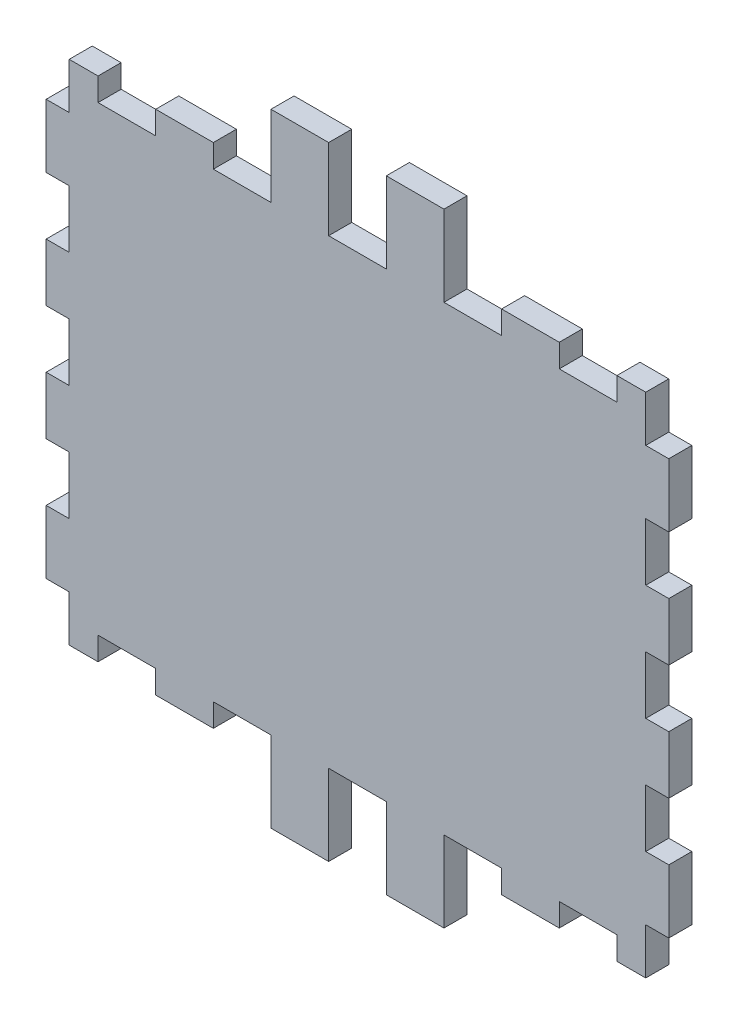
SolidWorks part; units mm, degrees
ref_plane "Front Plane" through (0, 0, 0) normal (0, 0, 1) x (1, 0, 0)
ref_plane "Top Plane" through (0, 0, 0) normal (0, 1, 0) x (1, 0, 0)
ref_plane "Right Plane" through (0, 0, 0) normal (1, 0, 0) x (0, 0, -1)
sketch "Sketch1" plane through (0, 0, 0) normal (0, 0, 1) x (1, 0, 0)
  line L0 (-50, 40) -> (-40, 40)
  line L1 (-50, -40) -> (50, -40)
  line L2 (-50, -40) -> (-50, 40)
  line L3 (-50, 40) -> (50, 40)
  line L4 (50, -40) -> (50, 40)
  line L5 (0, 40) -> (0, -40) construction
  line L6 (-50, 0) -> (50, 0) construction
  line L7 (-40, 40) -> (-30, 40)
  line L8 (-30, 40) -> (-20, 40)
  line L9 (-20, 40) -> (-10, 40)
  line L10 (-10, 40) -> (0, 40)
  line L11 (0, 40) -> (10, 40)
  line L12 (10, 40) -> (20, 40)
  line L13 (20, 40) -> (30, 40)
  line L14 (30, 40) -> (40, 40)
  line L15 (40, 40) -> (50, 40)
  line L16 (50, 20) -> (50, 0)
  line L17 (50, 0) -> (50, -20)
  line L18 (50, -20) -> (50, -40)
  line L19 (50, -40) -> (40, -40)
  line L20 (40, -40) -> (30, -40)
  line L21 (30, -40) -> (20, -40)
  line L22 (20, -40) -> (10, -40)
  line L23 (10, -40) -> (0, -40)
  line L24 (0, -40) -> (-10, -40)
  line L25 (-10, -40) -> (-20, -40)
  line L26 (-20, -40) -> (-30, -40)
  line L27 (-30, -40) -> (-40, -40)
  line L28 (-40, -40) -> (-50, -40)
  line L29 (-50, -20) -> (-50, 0)
  line L30 (-50, 0) -> (-50, 20)
  line L31 (-50, 20) -> (-50, 40)
  line L32 (50, -40) -> (50, -20) construction
  line L34 (-54, -35) -> (-46, -35)
  line L35 (-54, -35) -> (-54, -25)
  line L36 (-54, -25) -> (-46, -25)
  line L37 (-46, -35) -> (-46, -25)
  line L38 (-50, -25) -> (-50, -35) construction
  line L39 (-54, -30) -> (-46, -30) construction
  line L40 (-54, -15) -> (-46, -15)
  line L41 (-54, -15) -> (-54, -5)
  line L42 (-54, -5) -> (-46, -5)
  line L43 (-46, -15) -> (-46, -5)
  line L44 (-50, -5) -> (-50, -15) construction
  line L45 (-54, -10) -> (-46, -10) construction
  line L46 (-54, 5) -> (-46, 5)
  line L47 (-54, 5) -> (-54, 15)
  line L48 (-54, 15) -> (-46, 15)
  line L49 (-46, 5) -> (-46, 15)
  line L50 (-50, 15) -> (-50, 5) construction
  line L51 (-54, 10) -> (-46, 10) construction
  line L52 (-54, 25) -> (-46, 25)
  line L53 (-54, 25) -> (-54, 35)
  line L54 (-54, 35) -> (-46, 35)
  line L55 (-46, 25) -> (-46, 35)
  line L56 (-50, 35) -> (-50, 25) construction
  line L57 (-54, 30) -> (-46, 30) construction
  line L58 (46, 25) -> (54, 25)
  line L59 (46, 25) -> (46, 35)
  line L60 (46, 35) -> (54, 35)
  line L61 (54, 25) -> (54, 35)
  line L62 (50, 35) -> (50, 25) construction
  line L63 (46, 30) -> (54, 30) construction
  line L64 (46, 5) -> (54, 5)
  line L65 (46, 5) -> (46, 15)
  line L66 (46, 15) -> (54, 15)
  line L67 (54, 5) -> (54, 15)
  line L68 (50, 15) -> (50, 5) construction
  line L69 (46, 10) -> (54, 10) construction
  line L70 (46, -15) -> (54, -15)
  line L71 (46, -15) -> (46, -5)
  line L72 (46, -5) -> (54, -5)
  line L73 (54, -15) -> (54, -5)
  line L74 (50, -5) -> (50, -15) construction
  line L75 (46, -10) -> (54, -10) construction
  line L76 (46, -35) -> (54, -35)
  line L77 (46, -35) -> (46, -25)
  line L78 (46, -25) -> (54, -25)
  line L79 (54, -35) -> (54, -25)
  line L80 (50, -25) -> (50, -35) construction
  line L81 (46, -30) -> (54, -30) construction
  line L82 (-50, 40) -> (-45, 40)
  line L83 (-50, 40) -> (-50, 44)
  line L84 (-50, 44) -> (-45, 44)
  line L85 (-45, 40) -> (-45, 44)
  line L86 (-35, 40) -> (-25, 40)
  line L87 (-35, 40) -> (-35, 44)
  line L88 (-35, 44) -> (-25, 44)
  line L89 (-25, 40) -> (-25, 44)
  line L90 (-15, 40) -> (-5, 40)
  line L91 (-15, 40) -> (-15, 44)
  line L92 (-15, 44) -> (-5, 44)
  line L93 (-5, 40) -> (-5, 44)
  line L94 (5, 40) -> (15, 40)
  line L95 (5, 40) -> (5, 44)
  line L96 (5, 44) -> (15, 44)
  line L97 (15, 40) -> (15, 44)
  line L98 (25, 40) -> (35, 40)
  line L99 (25, 40) -> (25, 44)
  line L100 (25, 44) -> (35, 44)
  line L101 (35, 40) -> (35, 44)
  line L102 (50, 40) -> (45, 40)
  line L103 (50, 40) -> (50, 44)
  line L104 (50, 44) -> (45, 44)
  line L105 (45, 40) -> (45, 44)
  line L106 (-50, -40) -> (-45, -40)
  line L107 (-50, -40) -> (-50, -44)
  line L108 (-50, -44) -> (-45, -44)
  line L109 (-45, -40) -> (-45, -44)
  line L110 (-35, -40) -> (-25, -40)
  line L111 (-35, -40) -> (-35, -44)
  line L112 (-35, -44) -> (-25, -44)
  line L113 (-25, -40) -> (-25, -44)
  line L114 (-15, -40) -> (-5, -40)
  line L115 (-15, -40) -> (-15, -44)
  line L116 (-15, -44) -> (-5, -44)
  line L117 (-5, -40) -> (-5, -44)
  line L118 (5, -40) -> (15, -40)
  line L119 (5, -40) -> (5, -44)
  line L120 (5, -44) -> (15, -44)
  line L121 (15, -40) -> (15, -44)
  line L122 (25, -40) -> (35, -40)
  line L123 (25, -40) -> (25, -44)
  line L124 (25, -44) -> (35, -44)
  line L125 (35, -40) -> (35, -44)
  line L126 (50, -40) -> (45, -40)
  line L127 (50, -40) -> (50, -44)
  line L128 (50, -44) -> (45, -44)
  line L129 (45, -40) -> (45, -44)
  line L130 (-15, -44) -> (-5, -44)
  line L131 (-15, -44) -> (-15, -54)
  line L132 (-15, -54) -> (-5, -54)
  line L133 (-5, -44) -> (-5, -54)
  line L134 (5, -44) -> (15, -44)
  line L135 (5, -44) -> (5, -54)
  line L136 (5, -54) -> (15, -54)
  line L137 (15, -44) -> (15, -54)
  line L138 (-15, 44) -> (-5, 44)
  line L139 (-15, 44) -> (-15, 54)
  line L140 (-15, 54) -> (-5, 54)
  line L141 (-5, 44) -> (-5, 54)
  line L142 (5, 44) -> (15, 44)
  line L143 (5, 44) -> (5, 54)
  line L144 (5, 54) -> (15, 54)
  line L145 (15, 44) -> (15, 54)
  point P0 (0, 0)
  point P25 (50, -30)
  point P27 (50, -10)
  point P28 (50, 10)
  point P29 (50, 30)
  point P30 (-50, 30)
  point P31 (-50, 10)
  point P32 (-50, -10)
  point P33 (-50, -30)
  point P34 (-50, -30)
  point P38 (-50, -10)
  point P42 (-50, 10)
  point P46 (-50, 30)
  point P50 (50, 30)
  point P54 (50, 10)
  point P58 (50, -10)
  point P62 (50, -30)
  dimension "D1" = 80
  dimension "D2" = 100
  dimension "D3" = 10
  dimension "D4" = 10
  dimension "D5" = 10
  dimension "D6" = 10
  dimension "D7" = 10
  dimension "D8" = 10
  dimension "D9" = 10
  dimension "D10" = 10
  dimension "D11" = 10
  dimension "D12" = 10
  dimension "D13" = 10
  dimension "D14" = 10
  dimension "D15" = 10
  dimension "D16" = 10
  dimension "D17" = 10
  dimension "D18" = 10
  dimension "D19" = 20
  dimension "D20" = 20
  dimension "D21" = 20
  dimension "D22" = 20
  dimension "D23" = 20
  dimension "D24" = 20
  dimension "D25" = 10
  dimension "D26" = 10
  dimension "D27" = 10
  dimension "D28" = 10
  dimension "D29" = 10
  dimension "D30" = 10
  dimension "D31" = 10
  dimension "D32" = 10
  dimension "D33" = 8
  dimension "D34" = 8
  dimension "D35" = 8
  dimension "D36" = 8
  dimension "D37" = 10
  dimension "D38" = 10
  dimension "D39" = 10
  dimension "D40" = 10
  dimension "D41" = 8
  dimension "D42" = 8
  dimension "D43" = 8
  dimension "D44" = 8
  dimension "D45" = 10
  dimension "D46" = 10
  dimension "D47" = 10
  dimension "D48" = 10
  dimension "D49" = 4
  dimension "D50" = 4
  dimension "D51" = 4
  dimension "D52" = 4
  dimension "D53" = 4
  dimension "D54" = 4
  dimension "D55" = 5
  dimension "D56" = 10
  dimension "D57" = 10
  dimension "D58" = 10
  dimension "D59" = 10
  dimension "D60" = 5
  dimension "D61" = 10
  dimension "D62" = 10
  dimension "D63" = 10
  dimension "D64" = 10
  dimension "D65" = 10
  dimension "D66" = 5
  dimension "D67" = 10
  dimension "D68" = 10
  dimension "D69" = 10
  dimension "D70" = 10
  dimension "D71" = 5
  dimension "D72" = 10
  dimension "D73" = 10
  dimension "D74" = 10
  dimension "D75" = 10
  dimension "D76" = 10
  dimension "D77" = 4
  dimension "D78" = 4
  dimension "D79" = 4
  dimension "D80" = 4
  dimension "D81" = 4
  dimension "D82" = 4
  dimension "D83" = 10
  dimension "D84" = 10
  dimension "D85" = 10
  dimension "D86" = 10
extrude "Boss-Extrude1" add sketch "Sketch1" along normal blind 4 contours L77 L78 L4 L70 L71 L72 L64 L65 L66 L58 L59 L60 L3 L0 L2 L54 L55 L52 L48 L49 L46 L42 L43 L40 L36 L37 L34 L1 | L52 L55 L54 L31 | L54 L53 L52 L31 | L46 L49 L48 L30 | L48 L47 L46 L30 | L40 L43 L42 L29 | L42 L41 L40 L29 | L34 L37 L36 L2 | L36 L35 L34 L2 | L76 L79 L78 L18 | L78 L77 L76 L18 | L70 L73 L72 L17 | L72 L71 L70 L17 | L64 L67 L66 L16 | L66 L65 L64 L16 | L58 L61 L60 L4 | L60 L59 L58 L4 | L0 L85 L84 L83 | L3 L89 L88 L87 L7 | L3 L93 L92 L91 L9 | L3 L101 L100 L99 L13 | L3 L97 L96 L95 L11 | L105 L15 L103 L104 | L109 L1 L107 L108 | L113 L1 L27 L111 L112 | L121 L1 L23 L119 L120 | L125 L1 L21 L123 L124 | L19 L129 L128 L127 | L92 L141 L140 L139 | L96 L145 L144 L143 | L133 L116 L131 L132 | L137 L120 L135 L136
sketch "Sketch2" plane through (0, 0, 4) normal (0, 0, 1) x (1, 0, 0)
  line L1 (50, -35) -> (54, -35)
  line L2 (50, -35) -> (50, -36)
  line L3 (50, -36) -> (54, -36)
  line L4 (54, -35) -> (54, -36)
  line L5 (50, 35) -> (54, 35)
  line L6 (50, 35) -> (50, 36)
  line L7 (50, 36) -> (54, 36)
  line L8 (54, 35) -> (54, 36)
  line L9 (-50, -35) -> (-54, -35)
  line L10 (-50, -35) -> (-50, -36)
  line L11 (-50, -36) -> (-54, -36)
  line L12 (-54, -35) -> (-54, -36)
  line L13 (-50, 35) -> (-54, 35)
  line L14 (-50, 35) -> (-50, 36)
  line L15 (-50, 36) -> (-54, 36)
  line L16 (-54, 35) -> (-54, 36)
  dimension "D1" = 1
  dimension "D2" = 1
  dimension "D3" = 1
  dimension "D4" = 1
extrude "Boss-Extrude2" add sketch "Sketch2" against normal blind 4
